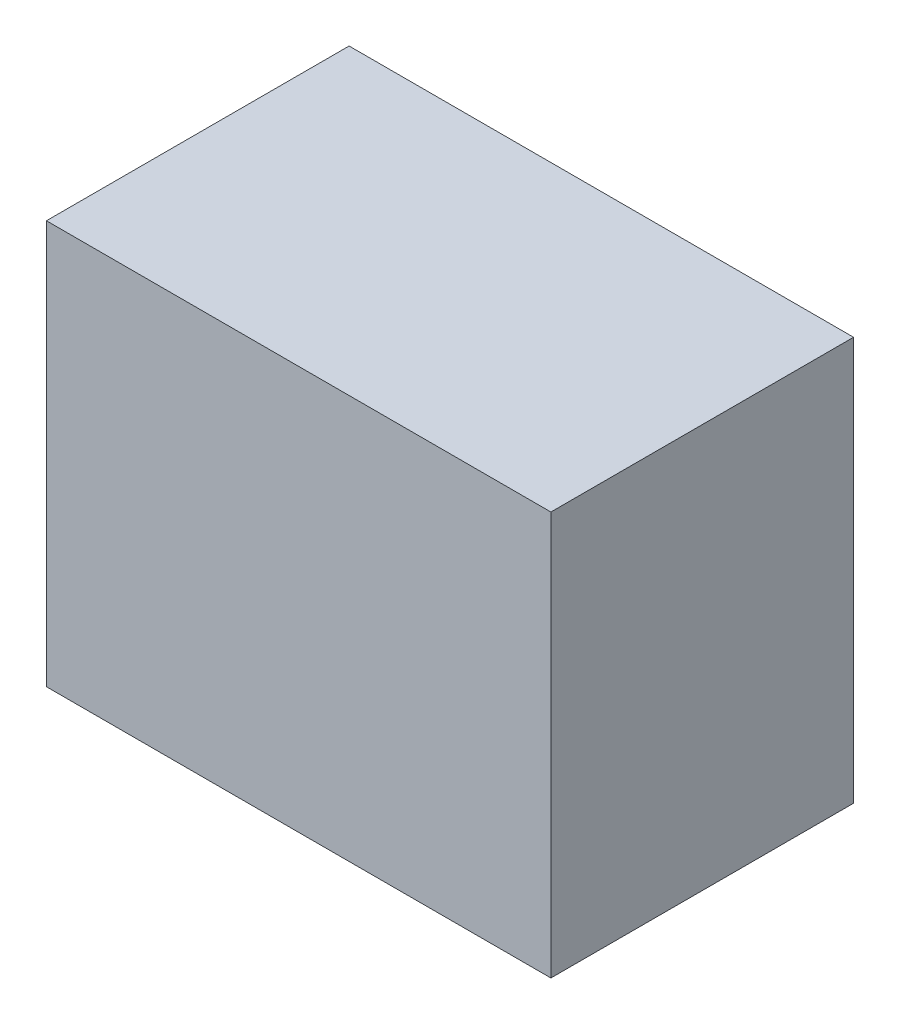
SolidWorks part; units mm, degrees
material "Custom Plastic"
ref_plane "Front Plane" through (0, 0, 0) normal (0, 0, 1) x (1, 0, 0)
ref_plane "Top Plane" through (0, 0, 0) normal (0, 1, 0) x (1, 0, 0)
ref_plane "Right Plane" through (0, 0, 0) normal (1, 0, 0) x (0, 0, -1)
sketch "Sketch1" plane through (0, 0, 0) normal (0, 0, 1) x (1, 0, 0)
  line L1 (-46.9008, 26.5496) -> (3.0992, 26.5496)
  line L2 (-46.9008, 26.5496) -> (-46.9008, -13.4504)
  line L3 (-46.9008, -13.4504) -> (3.0992, -13.4504)
  line L4 (3.0992, 26.5496) -> (3.0992, -13.4504)
  dimension "D1" = 50
  dimension "D2" = 40
extrude "Boss-Extrude1" add sketch "Sketch1" along normal blind 30
